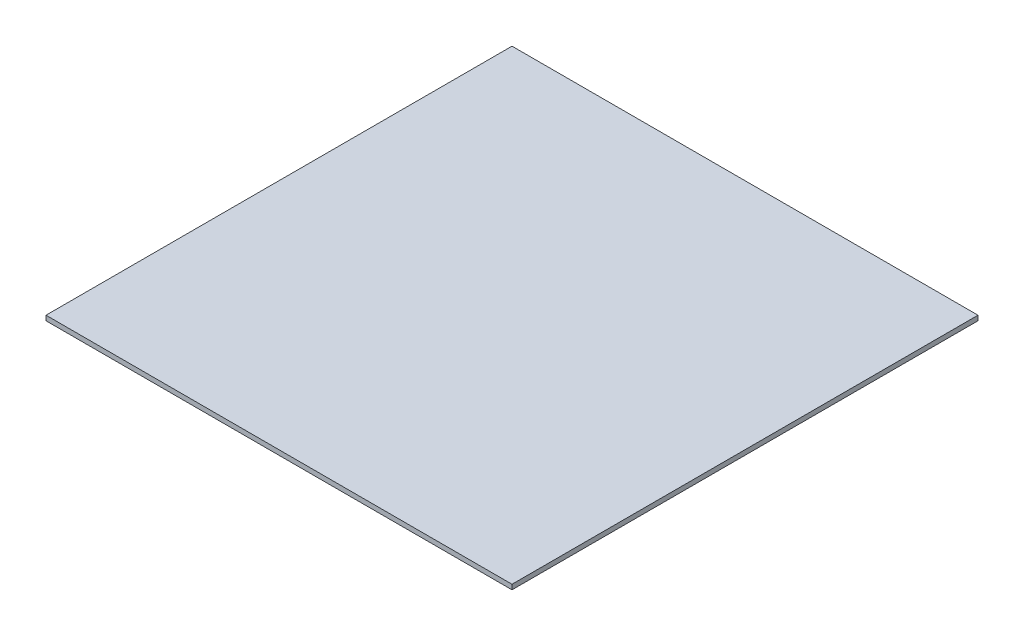
SolidWorks part; units mm, degrees
ref_plane "Front Plane" through (0, 0, 0) normal (0, 0, 1) x (1, 0, 0)
ref_plane "Top Plane" through (0, 0, 0) normal (0, 1, 0) x (1, 0, 0)
ref_plane "Right Plane" through (0, 0, 0) normal (1, 0, 0) x (0, 0, -1)
sketch "Sketch1" plane through (0, 0, 0) normal (0, 1, 0) x (1, 0, 0)
  line L1 (304.8, -304.8) -> (-304.8, -304.8)
  line L2 (304.8, -304.8) -> (304.8, 304.8)
  line L3 (304.8, 304.8) -> (-304.8, 304.8)
  line L4 (-304.8, -304.8) -> (-304.8, 304.8)
  line L5 (304.8, -304.8) -> (-304.8, 304.8) construction
  line L6 (304.8, 304.8) -> (-304.8, -304.8) construction
  point P0 (0, 0)
  dimension "Width" = 609.6
  dimension "Length" = 609.6
sketch "Sketch2" plane through (0, 0, 0) normal (1, 0, 0) x (0, 0, -1)
  line L0 (304.8, 3.175) -> (304.8, -3.175) construction
  point P3 (304.8, 0)
  dimension "Thickness" = 6.35
sketch "Sketch3" plane through (0, 0, 0) normal (0, 1, 0) x (1, 0, 0)
  line L4 (-304.8, -304.8) -> (304.8, -304.8)
  line L5 (-304.8, 304.8) -> (-304.8, -304.8)
  line L6 (304.8, 304.8) -> (-304.8, 304.8)
  line L7 (304.8, -304.8) -> (304.8, 304.8)
  line L8 (-304.8, -304.8) -> (304.8, -304.8)
  line L9 (-304.8, 304.8) -> (-304.8, -304.8)
  line L10 (304.8, 304.8) -> (-304.8, 304.8)
  line L11 (304.8, -304.8) -> (304.8, 304.8)
  dimension "D1" = 0
extrude "Boss-Extrude1" add sketch "Sketch3" along normal mid plane 6.35
equation "\"D1@Boss-Extrude1\"=\"Thickness@Sketch2\""
